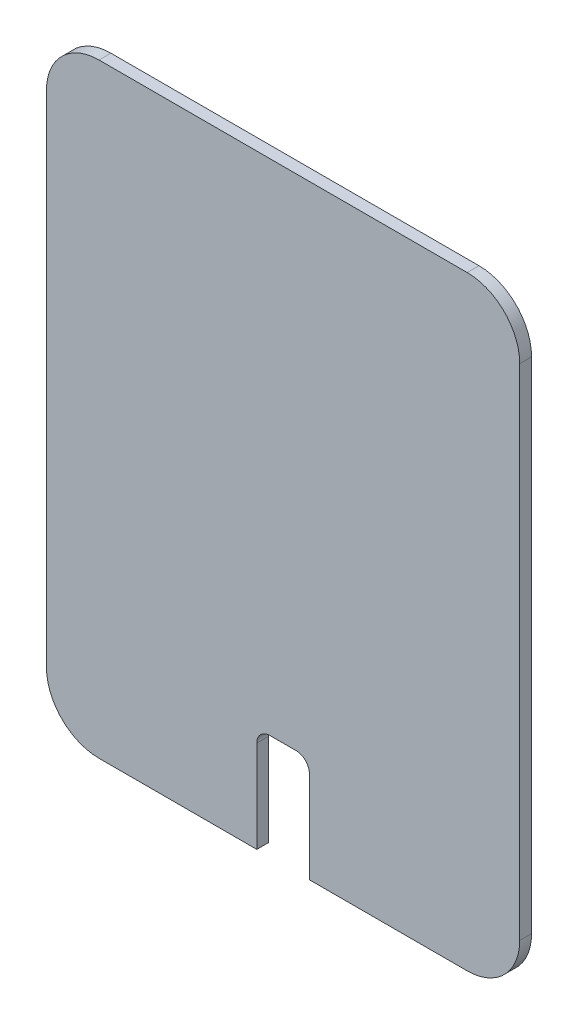
SolidWorks part; units mm, degrees
material "ABS PC"
ref_plane "前视基准面" through (0, 0, 0) normal (0, 0, 1) x (1, 0, 0)
ref_plane "上视基准面" through (0, 0, 0) normal (0, 1, 0) x (1, 0, 0)
ref_plane "右视基准面" through (0, 0, 0) normal (1, 0, 0) x (0, 0, -1)
sketch "草图1" plane through (0, 0, 0) normal (0, 0, 1) x (1, 0, 0)
  line L1 (-70, -115) -> (70, -115)
  line L2 (-90, -95) -> (-90, 95)
  line L3 (-70, 115) -> (70, 115)
  line L4 (90, -95) -> (90, 95)
  line L5 (-90, -115) -> (90, 115) construction
  line L6 (-90, 115) -> (90, -115) construction
  arc A0 (-70, -115) -> (-90, -95) centre (-70, -95) cw
  arc A1 (70, -115) -> (90, -95) centre (70, -95) ccw
  arc A2 (70, 115) -> (90, 95) centre (70, 95) cw
  arc A3 (-90, 95) -> (-70, 115) centre (-70, 95) cw
  point P0 (0, 0)
  dimension "D3" = 20
  dimension "D1" = 180
  dimension "D2" = 230
extrude "凸台-拉伸1" add sketch "草图1" along normal blind 4.5
sketch "草图2" plane through (0, 0, 4.5) normal (0, 0, 1) x (1, 0, 0)
  line L0 (0, 0) -> (0, -115) construction
  line L1 (-70, -115) -> (70, -115) construction
  line L3 (-10, -155) -> (10, -155)
  line L4 (-10, -155) -> (-10, -80)
  line L5 (-5, -75) -> (5, -75)
  line L6 (10, -155) -> (10, -80)
  line L7 (-10, -155) -> (10, -75) construction
  line L8 (-10, -75) -> (10, -155) construction
  arc A0 (5, -75) -> (10, -80) centre (5, -80) cw
  arc A1 (-10, -80) -> (-5, -75) centre (-5, -80) cw
  dimension "D3" = 5
  dimension "D1" = 20
  dimension "D2" = 80
extrude "切除-拉伸1" cut sketch "草图2" against normal blind 4.5
